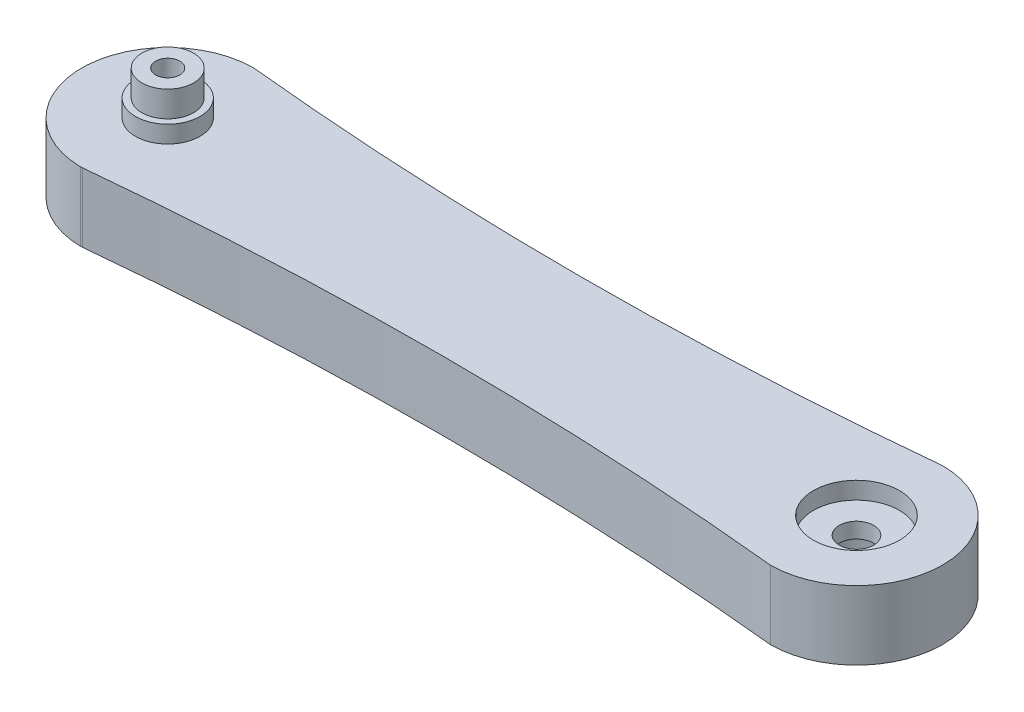
SolidWorks part; units mm, degrees
ref_plane "Front Plane" through (0, 0, 0) normal (0, 0, 1) x (1, 0, 0)
ref_plane "Top Plane" through (0, 0, 0) normal (0, 1, 0) x (1, 0, 0)
ref_plane "Right Plane" through (0, 0, 0) normal (1, 0, 0) x (0, 0, -1)
sketch "Sketch1" plane through (0, 0, 0) normal (0, 1, 0) x (1, 0, 0)
  line L1 (-40, -10) -> (40, -10)
  line L3 (-40, 10) -> (40, 10)
  line L5 (-40, -10) -> (40, 10) construction
  line L6 (-40, 10) -> (40, -10) construction
  arc A0 (-40, 10) -> (-40, -10) centre (-40, 0) ccw
  arc A1 (40, 10) -> (40, -10) centre (40, 0) cw
  circle A2 centre (-40, 0) radius 1.4
  circle A3 centre (40, 0) radius 2
  point P0 (0, 0)
  dimension "D1" = 10
  dimension "D3" = 2.8
  dimension "D4" = 4
  dimension "D2" = 80
extrude "Boss-Extrude1" add sketch "Sketch1" along normal blind 8
sketch "Sketch2" plane through (0, 8, 0) normal (0, 1, 0) x (1, 0, 0)
  circle A0 centre (-40, 0) radius 3.75
  dimension "D1" = 7.5
extrude "Boss-Extrude2" add sketch "Sketch2" along normal blind 2
sketch "Sketch3" plane through (0, 10, 0) normal (0, 1, 0) x (1, 0, 0)
  circle A0 centre (-40, 0) radius 3
  dimension "D1" = 6
extrude "Boss-Extrude3" add sketch "Sketch3" along normal blind 3
sketch "Sketch4" plane through (0, 0, 0) normal (0, -1, 0) x (1, 0, 0)
  circle A0 centre (-40, 0) radius 1.4
  dimension "D1" = 2.8
extrude "Cut-Extrude1" cut sketch "Sketch4" against normal through all
sketch "Sketch5" plane through (0, 0, 0) normal (0, -1, 0) x (1, 0, 0)
  circle A0 centre (-40, 0) radius 5
  dimension "D1" = 10
extrude "Cut-Extrude2" cut sketch "Sketch5" against normal offset from surface (6 mm away) 2 up to face at (-40, 8, -3.75)
sketch "Sketch6" plane through (0, 0, 0) normal (0, -1, 0) x (1, 0, 0)
  circle A0 centre (40, 0) radius 5.25
  dimension "D1" = 10.5
extrude "Cut-Extrude3" cut sketch "Sketch6" against normal blind 3.2
sketch "Sketch7" plane through (0, 8, 0) normal (0, 1, 0) x (1, 0, 0)
  circle A0 centre (40, 0) radius 5
  dimension "D1" = 10
extrude "Cut-Extrude4" cut sketch "Sketch7" against normal blind 2
sketch "Sketch8" plane through (0, 3.2, 0) normal (0, -1, 0) x (1, 0, 0)
  circle A0 centre (40, 0) radius 4
  dimension "D1" = 8
extrude "Cut-Extrude5" cut sketch "Sketch8" against normal blind 1
sketch "Sketch9" plane through (0, 8, 0) normal (0, 1, 0) x (1, 0, 0)
  line L0 (40, 10) -> (-40, 10) construction
  line L1 (-40, 10) -> (40, 10)
  arc A0 (40, 10) -> (-40, 10) centre (0, 407.995) cw
  arc A1 (40, -10) -> (40, 10) centre (40, 0) ccw construction
  arc A2 (-40, 10) -> (-40, -10) centre (-40, 0) ccw construction
  dimension "D1" = 400
extrude "Cut-Extrude6" cut sketch "Sketch9" against normal through all both and the other way through all
mirror "Mirror1" about plane through (0, 0, 0) normal (0, 0, 1) of "Cut-Extrude6"
fillet "Fillet1" radius 2 2 edges at (-40, 4, 10) (-40, 4, -10)
